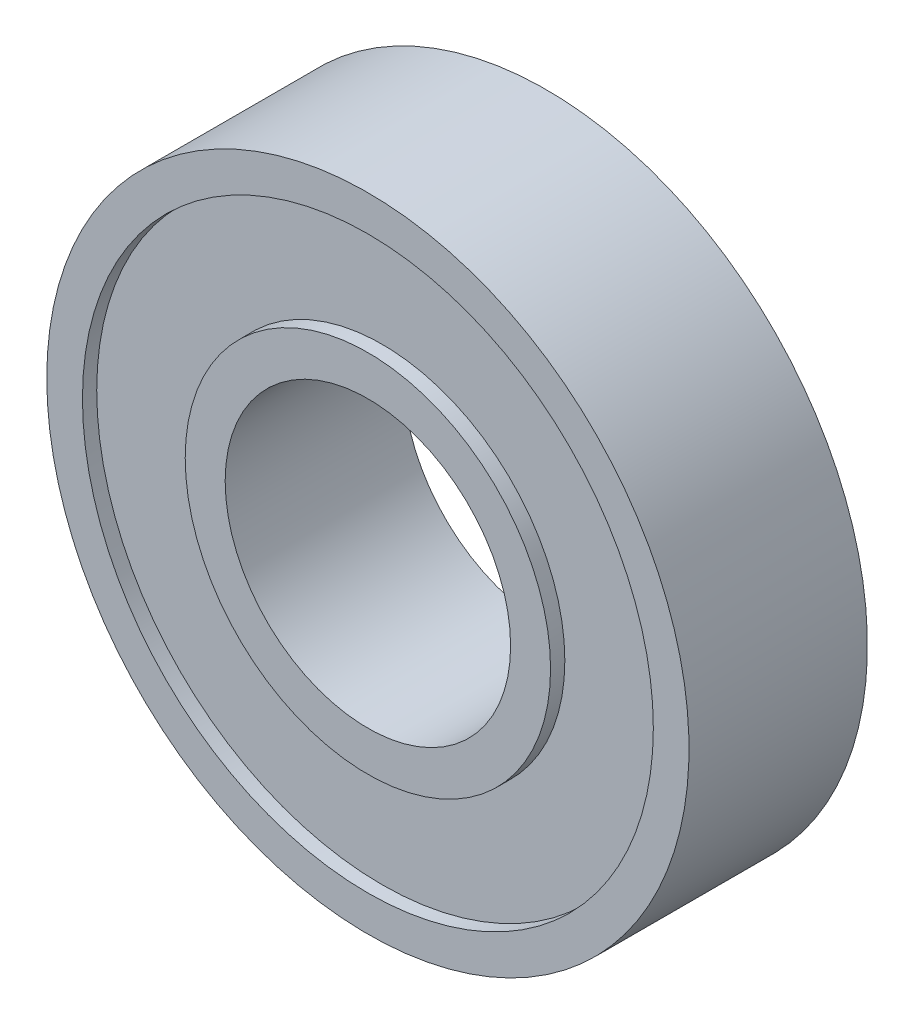
SolidWorks part; units mm, degrees
material "AISI 4130 Steel, annealed at 865C"
ref_plane "Front Plane" through (0, 0, 0) normal (0, 0, 1) x (1, 0, 0)
ref_plane "Top Plane" through (0, 0, 0) normal (0, 1, 0) x (1, 0, 0)
ref_plane "Right Plane" through (0, 0, 0) normal (1, 0, 0) x (0, 0, -1)
sketch "Sketch1" plane through (0, 0, 0) normal (0, 1, 0) x (1, 0, 0)
  line L0 (6.35, -3.9688) -> (8.128, -3.9688)
  line L1 (8.128, -3.9688) -> (8.128, -3.3338)
  line L2 (8.128, -3.3338) -> (12.7, -3.3338)
  line L3 (12.7, -3.3338) -> (12.7, -3.9688)
  line L4 (12.7, -3.9688) -> (14.2875, -3.9688)
  line L7 (14.2875, -2.3813) -> (14.2875, 3.9688)
  line L8 (14.2875, 3.9688) -> (12.7, 3.9688)
  line L9 (12.7, 3.9688) -> (12.7, 3.3338)
  line L10 (12.7, 3.3338) -> (8.128, 3.3338)
  line L11 (8.128, 3.3338) -> (8.128, 3.9688)
  line L12 (8.128, 3.9688) -> (6.35, 3.9688)
  line L13 (6.35, 3.9688) -> (6.35, -3.9688)
  line L14 (0, 3.9688) -> (0, -3.9688) construction
  line L15 (14.2875, -2.3813) -> (14.2875, -3.9688)
  line L16 (14.2875, -3.9688) -> (14.2875, -2.3813)
  dimension "D1" = 4.572
  dimension "D2" = 1.778
  dimension "D3" = 7.9375
  dimension "D6" = 1.5875
  dimension "D7" = 6.35
revolve "Revolve1" add sketch "Sketch1" angle 360 about L14
